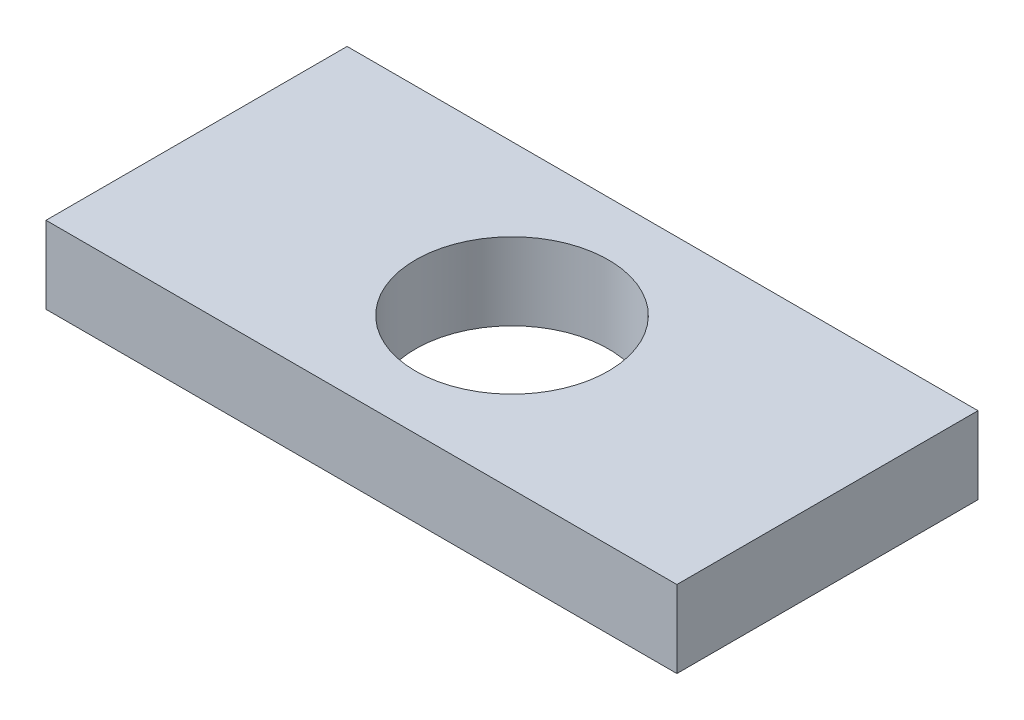
SolidWorks part; units mm, degrees
ref_plane "Front Plane" through (0, 0, 0) normal (0, 0, 1) x (1, 0, 0)
ref_plane "Top Plane" through (0, 0, 0) normal (0, 1, 0) x (1, 0, 0)
ref_plane "Right Plane" through (0, 0, 0) normal (1, 0, 0) x (0, 0, -1)
sketch "Sketch1" plane through (0, 0, 0) normal (0, 1, 0) x (1, 0, 0)
  line L1 (-41.5522, -19.8318) -> (41.5522, -19.8318)
  line L2 (-41.5522, -19.8318) -> (-41.5522, 19.8318)
  line L3 (-41.5522, 19.8318) -> (41.5522, 19.8318)
  line L4 (41.5522, -19.8318) -> (41.5522, 19.8318)
  line L5 (-41.5522, -19.8318) -> (41.5522, 19.8318) construction
  line L6 (-41.5522, 19.8318) -> (41.5522, -19.8318) construction
  circle A0 centre (0, 0) radius 12.7
  point P0 (0, 0)
  dimension "D3" = 25.4
  dimension "D1" = 83.1045
  dimension "D2" = 39.6635
extrude "Boss-Extrude1" add sketch "Sketch1" along normal blind 10.16
